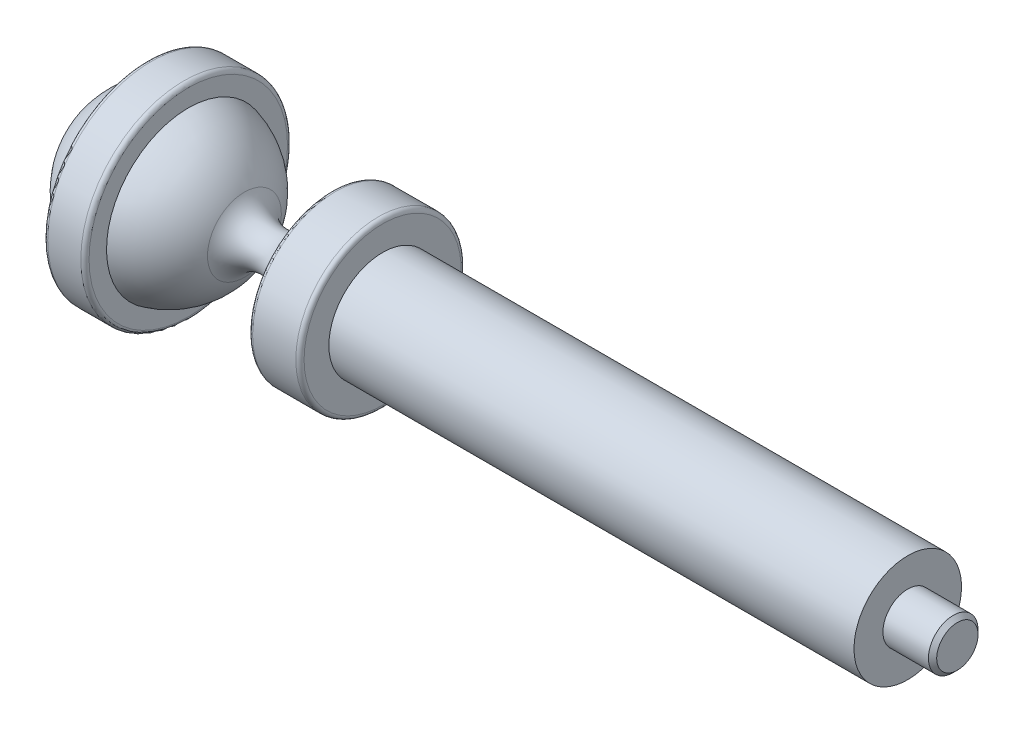
SolidWorks part; units mm, degrees
ref_plane "Front Plane" through (0, 0, 0) normal (0, 0, 1) x (1, 0, 0)
ref_plane "Top Plane" through (0, 0, 0) normal (0, 1, 0) x (1, 0, 0)
ref_plane "Right Plane" through (0, 0, 0) normal (1, 0, 0) x (0, 0, -1)
sketch "Sketch1" plane through (0, 0, 0) normal (0, 0, 1) x (1, 0, 0)
  line L8 (0, 0) -> (105.5, 0)
  line L12 (99.5, 6.5) -> (36, 6.5)
  line L13 (36, 10) -> (30, 10)
  line L14 (36, 6.5) -> (36, 10)
  line L15 (30, 10) -> (26.2613, 4.0845)
  line L16 (7.5, 9.8056) -> (7.5, 12.5)
  line L17 (7.5, 12.5) -> (12.5, 12.5)
  line L18 (12.5, 12.5) -> (12.5, 9.8869)
  line L19 (99.5, 6.5) -> (99.5, 3)
  line L20 (99.5, 3) -> (105, 3)
  line L21 (105.5, 2.5) -> (105.5, 0)
  line L22 (105, 3) -> (105.5, 2.5)
  arc A2 (26.2613, 4.0845) -> (19.2868, 4.464) centre (22.88, 6.2215) cw
  arc A4 (19.2868, 4.464) -> (12.5, 9.8869) centre (10.16, 0) ccw
  arc A5 (7.5, 9.8056) -> (0, 0) centre (10.16, 0) ccw
  point P17 (105.5, 3)
  dimension "D6" = 4
  dimension "D15" = 10.16
  dimension "D2" = 30
  dimension "D3" = 5
  dimension "D4" = 12.5
  dimension "D5" = 7.5
  dimension "D7" = 22.88
  dimension "D8" = 10
  dimension "D9" = 6
  dimension "D10" = 63.5
  dimension "D11" = 6.5
  dimension "D12" = 6
  dimension "D13" = 3
  dimension "D14" = 6.5
revolve "Revolve1" add sketch "Sketch1" angle 360 about L8
cosmetic thread "Cosmetic Thread1" parameters "D2"=4.891
fillet "Fillet1" radius 0.5 4 edges at (36, 0, 10) (30, 0, 10) (12.5, 0, 12.5) (7.5, 0, 12.5)
